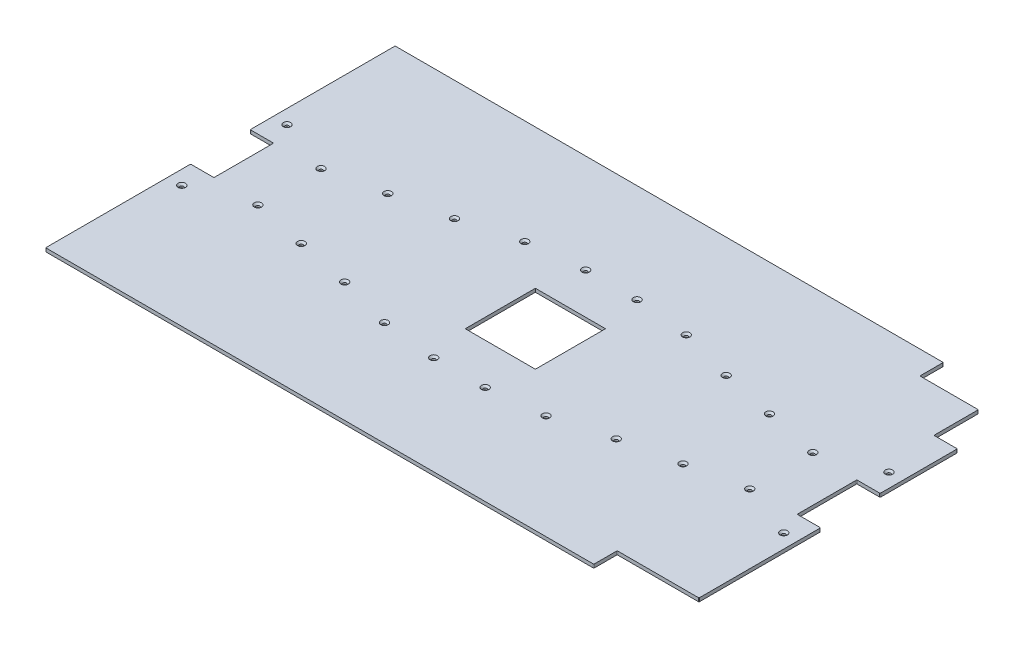
SolidWorks part; units mm, degrees
ref_plane "Front Plane" through (0, 0, 0) normal (0, 0, 1) x (1, 0, 0)
ref_plane "Top Plane" through (0, 0, 0) normal (0, 1, 0) x (1, 0, 0)
ref_plane "Right Plane" through (0, 0, 0) normal (1, 0, 0) x (0, 0, -1)
sketch "Sketch1" plane through (0, 0, 0) normal (0, 1, 0) x (1, 0, 0)
  line L1 (269.5, -149.5) -> (-269.5, -149.5)
  line L2 (269.5, -149.5) -> (269.5, 149.5)
  line L3 (269.5, 149.5) -> (-269.5, 149.5)
  line L4 (-269.5, -149.5) -> (-269.5, 149.5)
  line L5 (269.5, -149.5) -> (-269.5, 149.5) construction
  line L6 (269.5, 149.5) -> (-269.5, -149.5) construction
  point P0 (0, 0)
  dimension "D1" = 539
  dimension "D2" = 299
extrude "Boss-Extrude1" add sketch "Sketch1" along normal blind 3
sketch "Sketch2" plane through (0, 3, 0) normal (0, 1, 0) x (1, 0, 0)
  line L0 (0, 0) -> (-269.5, 0) construction
  line L1 (-269.5, 149.5) -> (-269.5, -149.5) construction
  line L3 (-249.5, -25.5) -> (-269.5, -25.5)
  line L4 (-249.5, -25.5) -> (-249.5, 25.5)
  line L5 (-249.5, 25.5) -> (-269.5, 25.5)
  line L6 (-269.5, -25.5) -> (-269.5, 25.5)
  line L7 (-249.5, -25.5) -> (-269.5, 25.5) construction
  line L8 (-249.5, 25.5) -> (-269.5, -25.5) construction
  point P5 (-259.5, 0)
  dimension "D1" = 20
  dimension "D2" = 51
extrude "Cut-Extrude1" cut sketch "Sketch2" against normal through all
mirror "Mirror1" about plane through (0, 0, 0) normal (1, 0, 0) of "Cut-Extrude1"
sketch "Sketch3" plane through (0, 3, 0) normal (0, 1, 0) x (1, 0, 0)
  point P0 (-255, -105)
  dimension "D1" = 255
  dimension "D2" = 105
sketch "Sketch8" plane through (0, 3, 0) normal (0, 1, 0) x (1, 0, 0)
  circle A1 centre (-69.1, -60) radius 2.5
  circle A2 centre (-69.1, -60) radius 2.5
  circle A3 centre (-116.2, -47.0034) radius 2.5
  circle A4 centre (-116.2, -47.0034) radius 2.5
  circle A5 centre (-163.3, -36.992) radius 2.5
  circle A6 centre (-163.3, -36.992) radius 2.5
  circle A7 centre (-210.4, -26.9806) radius 2.5
  circle A8 centre (-210.4, -26.9806) radius 2.5
  circle A9 centre (-257.5, -45) radius 2.5
  circle A10 centre (-257.5, -45) radius 2.5
  circle A11 centre (-22, -65) radius 2.5
  circle A12 centre (-22, -65) radius 2.5
  dimension "D1" = 0
  dimension "D2" = 0
  dimension "D3" = 0
  dimension "D4" = 0
  dimension "D5" = 0
  dimension "D6" = 0
hole_wizard "CSK for M3 Flat Head Machine Screw1" positions "3DSketch1" profile "Sketch4" countersink size "M3" standard "ANSI Metric" end condition through all
sketch3d "3DSketch1"
  point P3 (-257.5, 3, 45)
  point P6 (-210.4, 3, 26.9806)
  point P9 (-163.3, 3, 36.992)
  point P12 (-116.2, 3, 47.0034)
  point P15 (-69.1, 3, 60)
  point P18 (-22, 3, 65)
sketch "Sketch4" plane through (-257.5, 3, 45) normal (1, 0, 0) x (0, 0, 1)
  line L0 (0, 0) -> (0, 3)
  line L1 (0, 3) -> (1.6, 3)
  line L2 (1.6, 3) -> (1.6, 1.55)
  line L3 (1.6, 1.55) -> (3.15, 0)
  line L5 (3.15, 0) -> (0, 0)
  line L6 (-1.6, 1.55) -> (-3.15, 0) construction
  line L11 (0, -6.35) -> (0, 107.95) construction
  dimension "Thru Hole Dia." = 3.2
  dimension "Thru Hole Depth" = 3
  dimension "Near C'Sink Dia." = 6.3
  dimension "Near C'Sink Angle" = 90
sketch "Sketch6" plane through (0, 3, 0) normal (0, 1, 0) x (1, 0, 0)
  line L0 (199.5, 149.5) -> (199.5, 129.5)
  line L1 (269.5, 149.5) -> (-269.5, 149.5) construction
  line L2 (199.5, 129.5) -> (249.5, 129.5)
  line L3 (249.5, 129.5) -> (249.5, 91.5)
  line L4 (249.5, 91.5) -> (269.5, 91.5)
  line L6 (269.5, 25.5) -> (269.5, 149.5) construction
  line L7 (199.5, 149.5) -> (269.5, 149.5)
  line L8 (269.5, -149.5) -> (199.5, -149.5)
  line L9 (269.5, -149.5) -> (269.5, -129.5)
  line L10 (269.5, -129.5) -> (199.5, -129.5)
  line L11 (199.5, -149.5) -> (199.5, -129.5)
  line L12 (269.5, 149.5) -> (269.5, 91.5)
  dimension "D1" = 58
  dimension "D2" = 20
  dimension "D3" = 70
  dimension "D4" = 20
  dimension "D5" = 70
  dimension "D6" = 20
extrude "Cut-Extrude3" cut sketch "Sketch6" against normal through all and the other way through all
mirror "Mirror2" about plane through (0, 0, 0) normal (1, 0, 0) of "CSK for M3 Flat Head Machine Screw1"
mirror "Mirror3" about plane through (0, 0, 0) normal (0, 0, 1) of "Mirror2", "CSK for M3 Flat Head Machine Screw1"
sketch "Sketch9" plane through (0, 3, 0) normal (0, 1, 0) x (1, 0, 0)
  line L1 (30, -30) -> (-30, -30)
  line L2 (30, -30) -> (30, 30)
  line L3 (30, 30) -> (-30, 30)
  line L4 (-30, -30) -> (-30, 30)
  line L5 (30, -30) -> (-30, 30) construction
  line L6 (30, 30) -> (-30, -30) construction
  point P0 (0, 0)
  dimension "D1" = 60
  dimension "D2" = 60
extrude "Cut-Extrude4" cut sketch "Sketch9" against normal through all
fillet "Fillet1" radius 0.5 18 edges at (249.5, 1.5, -129.5) (199.5, 1.5, -129.5) (199.5, 1.5, -149.5) (-269.5, 1.5, -149.5) (-249.5, 1.5, -25.5) (-249.5, 1.5, 25.5) (-269.5, 1.5, 25.5) (-269.5, 1.5, 149.5) (199.5, 1.5, 149.5) (199.5, 1.5, 129.5) (269.5, 1.5, 129.5) (269.5, 1.5, 25.5) (249.5, 1.5, 25.5) (249.5, 1.5, -25.5) (269.5, 1.5, -25.5) (269.5, 1.5, -91.5) (249.5, 1.5, -91.5) (-269.5, 1.5, -25.5)
